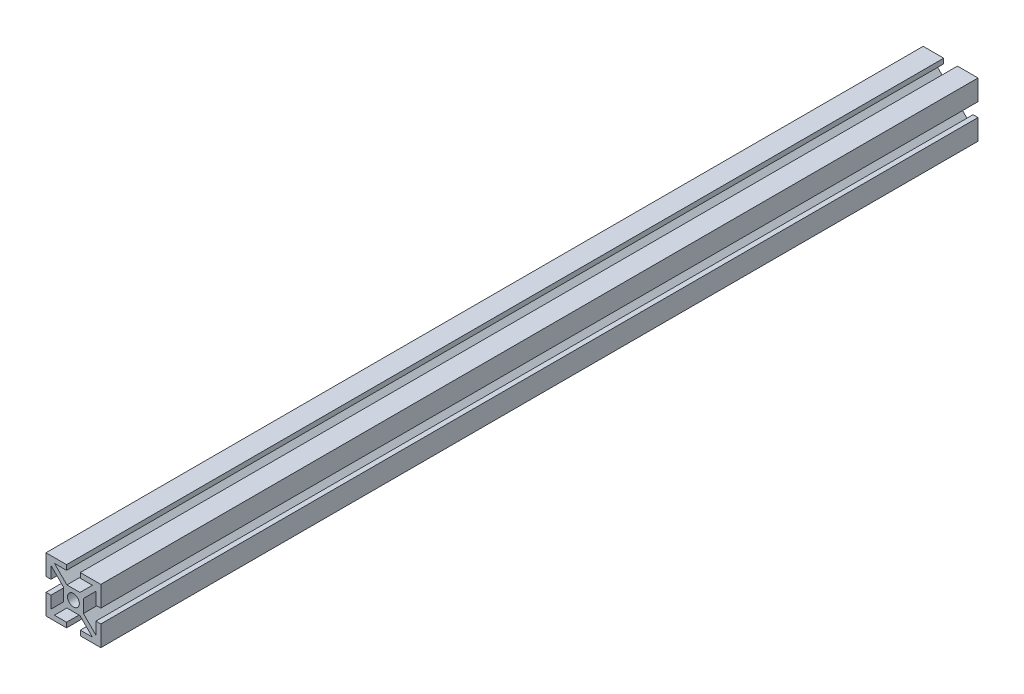
SolidWorks part; units mm, degrees
ref_plane "Plan de face" through (0, 0, 0) normal (0, 0, 1) x (1, 0, 0)
ref_plane "Plan de dessus" through (0, 0, 0) normal (0, 1, 0) x (1, 0, 0)
ref_plane "Plan de droite" through (0, 0, 0) normal (1, 0, 0) x (0, 0, -1)
sketch "Esquisse1" plane through (0, 0, 0) normal (0, 0, 1) x (1, 0, 0)
  line L0 (20, 12.5) -> (18.2, 12.5)
  line L1 (0, 0) -> (7.5, 0)
  line L2 (0, 0) -> (0, 7.5)
  line L3 (0, 20) -> (7.5, 20)
  line L4 (20, 0) -> (20, 7.5)
  line L5 (18.2, 12.5) -> (18.2, 16.9272)
  line L6 (0, 0) -> (20, 20) construction
  line L7 (13.65, 12.3772) -> (13.65, 10)
  line L8 (13.65, 12.3772) -> (18.2, 16.9272)
  line L9 (12.5, 20) -> (12.5, 18.2)
  line L10 (12.5, 18.2) -> (16.9272, 18.2)
  line L11 (12.3772, 13.65) -> (16.9272, 18.2)
  line L12 (12.3772, 13.65) -> (10, 13.65)
  line L13 (13.65, 7.6228) -> (13.65, 10)
  line L14 (13.65, 7.6228) -> (18.2, 3.0728)
  line L15 (18.2, 7.5) -> (18.2, 3.0728)
  line L16 (20, 7.5) -> (18.2, 7.5)
  line L17 (12.5, 1.8) -> (16.9272, 1.8)
  line L18 (12.3772, 6.35) -> (16.9272, 1.8)
  line L19 (12.5, 0) -> (12.5, 1.8)
  line L20 (12.3772, 6.35) -> (10, 6.35)
  line L21 (7.6228, 6.35) -> (10, 6.35)
  line L22 (7.6228, 6.35) -> (3.0728, 1.8)
  line L23 (7.5, 1.8) -> (3.0728, 1.8)
  line L24 (7.5, 0) -> (7.5, 1.8)
  line L25 (1.8, 7.5) -> (1.8, 3.0728)
  line L26 (6.35, 7.6228) -> (1.8, 3.0728)
  line L27 (0, 7.5) -> (1.8, 7.5)
  line L28 (6.35, 7.6228) -> (6.35, 10)
  line L29 (6.35, 12.3772) -> (6.35, 10)
  line L30 (6.35, 12.3772) -> (1.8, 16.9272)
  line L31 (1.8, 12.5) -> (1.8, 16.9272)
  line L32 (0, 12.5) -> (1.8, 12.5)
  line L33 (7.5, 18.2) -> (3.0728, 18.2)
  line L34 (7.6228, 13.65) -> (3.0728, 18.2)
  line L35 (7.5, 20) -> (7.5, 18.2)
  line L36 (7.6228, 13.65) -> (10, 13.65)
  line L37 (20, 12.5) -> (20, 20)
  line L38 (12.5, 20) -> (20, 20)
  line L39 (0, 12.5) -> (0, 20)
  line L40 (12.5, 0) -> (20, 0)
  circle A0 centre (10, 10) radius 2.15
  point P51 (10, 10)
  dimension "D2" = 4.3
  dimension "D1" = 20
  dimension "D3" = 1.8
  dimension "D4" = 5
  dimension "D5" = 6.35
  dimension "D6" = 1.8
  dimension "D7" = 4
extrude "Boss.-Extru.1" add sketch "Esquisse1" along normal blind 320
